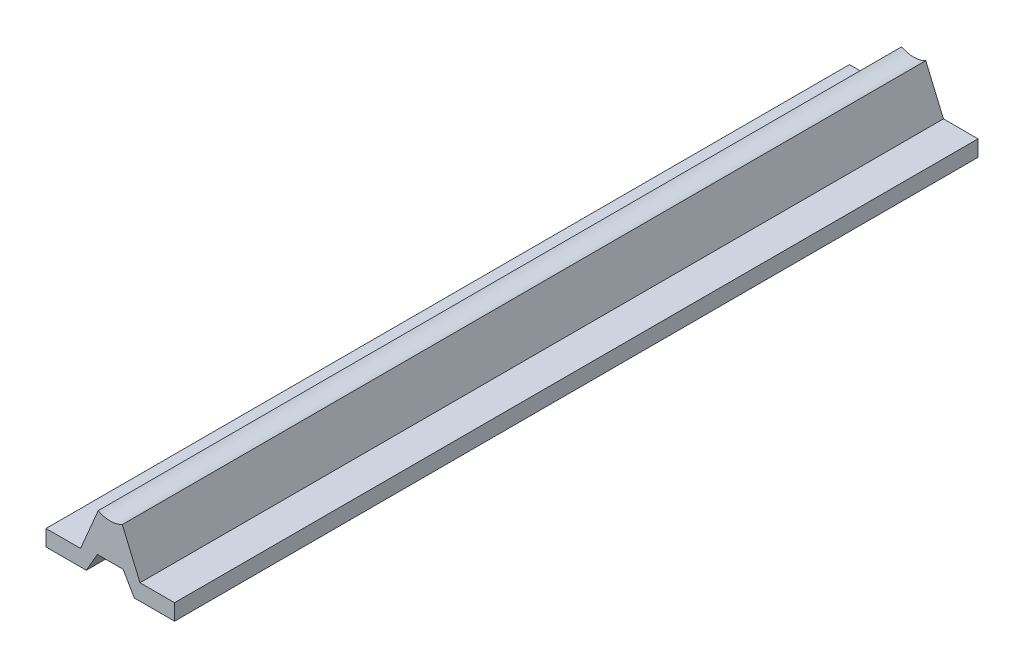
SolidWorks part; units mm, degrees
material "6063-T5"
ref_plane "Front Plane" through (0, 0, 0) normal (0, 0, 1) x (1, 0, 0)
ref_plane "Top Plane" through (0, 0, 0) normal (0, 1, 0) x (1, 0, 0)
ref_plane "Right Plane" through (0, 0, 0) normal (1, 0, 0) x (0, 0, -1)
sketch "Sketch1" plane through (0, 0, 0) normal (0, 0, 1) x (1, 0, 0)
  line L0 (-20, -25) -> (-7.4641, -25)
  line L1 (-7.4641, -25) -> (-4, -19)
  line L2 (-4, -19) -> (4, -19)
  line L3 (4, -19) -> (7.4641, -25)
  line L4 (7.4641, -25) -> (20, -25)
  line L5 (20, -25) -> (20, -20)
  line L6 (20, -20) -> (9.25, -20)
  line L10 (-20, -25) -> (-20, -20)
  line L11 (-20, -20) -> (-9.25, -20)
  line L15 (-9.25, -20) -> (-3.75, -7.0666)
  line L16 (0, -8) -> (0, 0) construction
  line L17 (3.75, -7.0666) -> (9.25, -20)
  line L18 (0, -8) -> (0, -19) construction
  arc A0 (-3.75, -7.0666) -> (3.75, -7.0666) centre (0, 0) ccw
  dimension "D1" = 8
  dimension "D2" = 7.5
  dimension "D3" = 5
  dimension "D4" = 25
  dimension "D5" = 18.5
  dimension "D7" = 20
  dimension "D10" = 8
  dimension "D11" = 60
  dimension "D12" = 6
  dimension "D13" = 40
extrude "Boss-Extrude1" add sketch "Sketch1" along normal blind 250
ref_plane "Плоскость1" through (0, 0, 0) normal (1, 0, 0) x (0, 0, -1)
equation "\"SBR16.Length.X\"= 600мм"
equation "\"SBR16.Length.Y\"= 500мм"
equation "\"SBR16.Length.Z\"= 250мм"
equation "\"D1@Boss-Extrude1\"= \"SBR16.Length.Z\""
